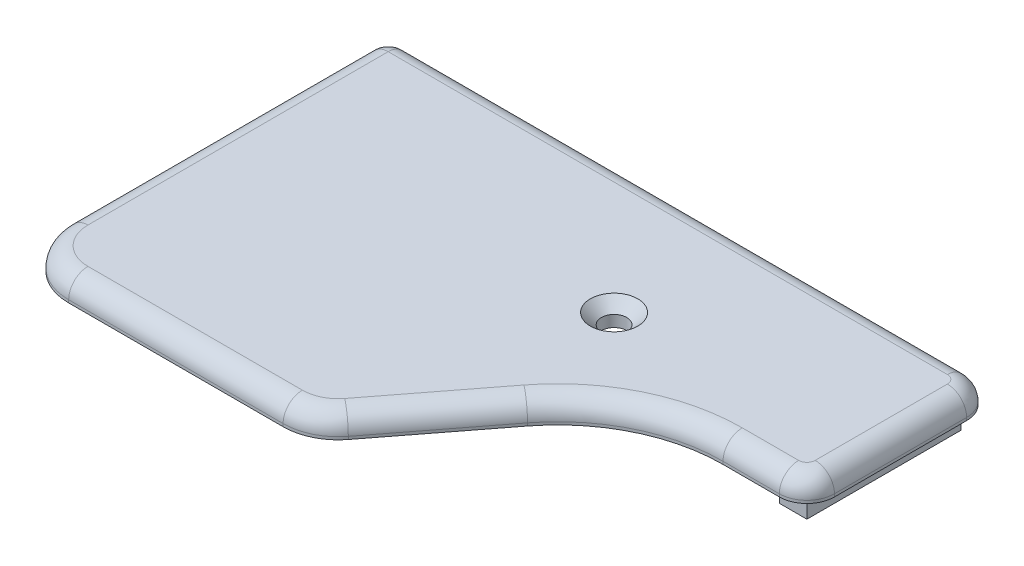
SolidWorks part; units mm, degrees
ref_plane "Front Plane" through (0, 0, 0) normal (0, 0, 1) x (1, 0, 0)
ref_plane "Top Plane" through (0, 0, 0) normal (0, 1, 0) x (1, 0, 0)
ref_plane "Right Plane" through (0, 0, 0) normal (1, 0, 0) x (0, 0, -1)
sketch "Sketch1" plane through (0, 0, 0) normal (0, 1, 0) x (1, 0, 0)
  line L5 (0, 0) -> (69.85, 0)
  line L6 (69.85, 0) -> (69.85, -21.59)
  line L7 (69.85, -21.59) -> (50.8, -21.59)
  line L8 (50.8, -21.59) -> (38.1, -38.1)
  line L9 (38.1, -38.1) -> (0, -38.1) construction
  line L10 (0, -38.1) -> (0, 0)
  line L11 (0, -38.1) -> (0, -43.18)
  line L12 (0, -43.18) -> (34.1923, -43.18)
  line L13 (34.1923, -43.18) -> (38.1, -38.1)
  circle A0 centre (41.275, -15.24) radius 1.4605
  dimension "D7" = 2.921
  dimension "D1" = 38.1
  dimension "D2" = 38.1
  dimension "D3" = 69.85
  dimension "D4" = 21.59
  dimension "D5" = 19.05
  dimension "D6" = 5.08
  dimension "D8" = 28.575
  dimension "D9" = 6.35
extrude "Boss-Extrude1" add sketch "Sketch1" along normal blind 2.54
sketch "Sketch12" plane through (0, 0, 0) normal (0, -1, 0) x (1, 0, 0)
  line L0 (69.85, 21.59) -> (69.85, 0) construction
  line L1 (64.77, 19.685) -> (67.945, 19.685)
  line L2 (64.77, 19.685) -> (64.77, 1.905)
  line L3 (64.77, 1.905) -> (67.945, 1.905)
  line L4 (67.945, 19.685) -> (67.945, 1.905)
  line L5 (50.8, 21.59) -> (69.85, 21.59) construction
  line L6 (69.85, 0) -> (0, 0) construction
  dimension "D1" = 1.905
  dimension "D2" = 1.905
  dimension "D3" = 1.905
  dimension "D4" = 3.175
extrude "Boss-Extrude7" add sketch "Sketch12" along normal blind 2.54
fillet "Fillet6" radius 19.05 1 edges at (50.8, 1.27, 21.59)
fillet "Fillet7" radius 6.35 2 edges at (0, 1.27, 43.18) (34.1923, 1.27, 43.18)
fillet "Fillet8" radius 3.175 2 edges at (69.85, 1.27, 0) (69.85, 1.27, 21.59)
fillet "Fillet9" radius 2.2225 1 edges at (0, 1.27, 0)
chamfer "Chamfer1" distance 1.27 angle 44 1 edges at (41.275, 2.54, 16.7005)
fillet "Fillet10" radius 2.2225 12 edges at (0.651, 2.54, 0.651) (34.4487, 2.54, 0) (68.9201, 2.54, 0.9299) (69.85, 2.54, 10.795) (68.9201, 2.54, 20.6601) (63.4276, 2.54, 21.59) (51.7649, 2.54, 23.5495) (40.5897, 2.54, 34.8633) (33.8707, 2.54, 42.5268) (18.7078, 2.54, 43.18) (1.8599, 2.54, 41.3201) (0, 2.54, 19.5263)
